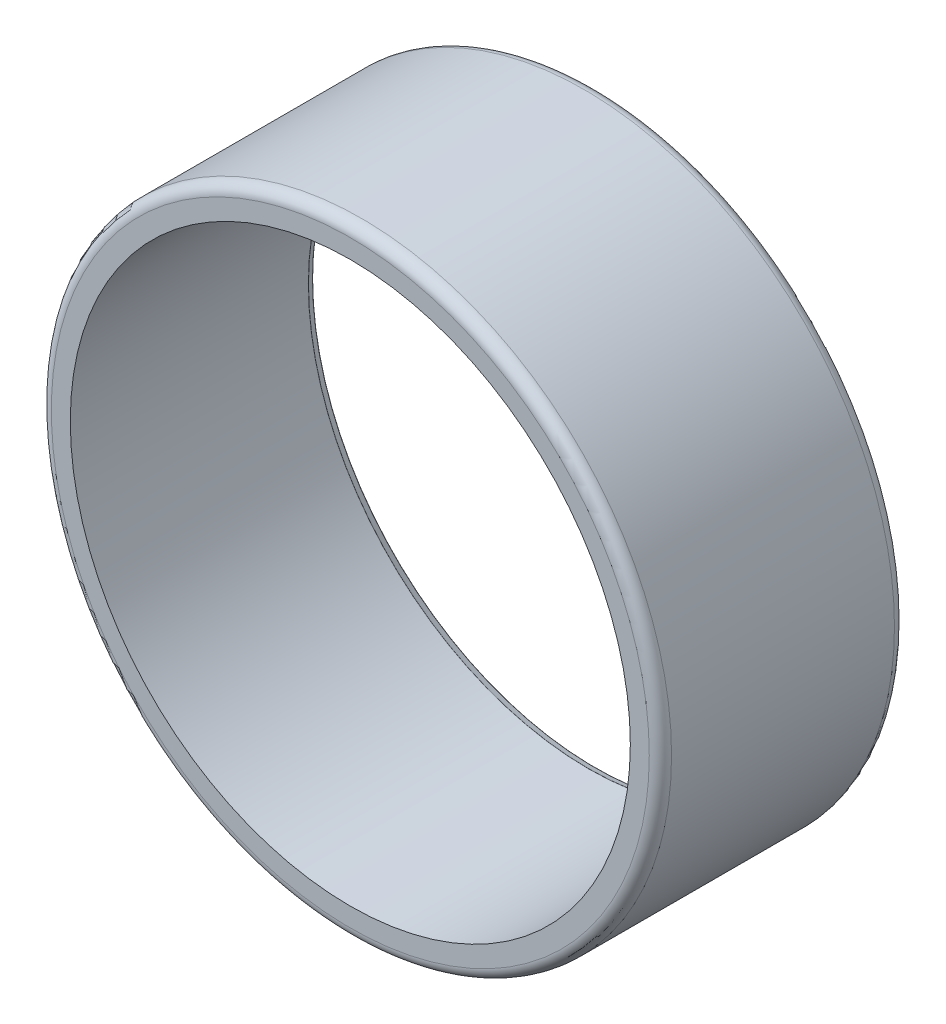
SolidWorks part; units mm, degrees
material "AISI 1018 Low Carbon Steel"
ref_plane "Front Plane" through (0, 0, 0) normal (0, 0, 1) x (1, 0, 0)
ref_plane "Top Plane" through (0, 0, 0) normal (0, 1, 0) x (1, 0, 0)
ref_plane "Right Plane" through (0, 0, 0) normal (1, 0, 0) x (0, 0, -1)
ref_axis "CL" through (0, 0, 55) along (0, 0, -1)
sketch "Sketch1" plane through (0, 0, 0) normal (1, 0, 0) x (0, 0, -1)
  line L0 (0, 27.825) -> (0, 0) construction
  line L1 (-9.96, 0) -> (9.96, 0) construction
  line L2 (-10, 27.825) -> (10, 27.825)
  line L3 (-11, 26.825) -> (-11, 25.125)
  line L4 (-11, 25.125) -> (11, 25.125)
  line L7 (11, 26.825) -> (11, 25.125)
  line L8 (10.3681, 25.125) -> (11, 25.355)
  arc A0 (-10, 27.825) -> (-11, 26.825) centre (-10, 26.825) ccw
  arc A1 (10, 27.825) -> (11, 26.825) centre (10, 26.825) cw
  point P9 (0, 0)
  point P13 (-11, 27.825)
  point P16 (11, 27.825)
  dimension "D4" = 1
  dimension "D5" = 1
  dimension "D1" = 50.25
  dimension "D2" = 22
  dimension "D3" = 55.65
  dimension "D6" = 20
  dimension "D7" = 0.23
revolve "Revolve1" add sketch "Sketch1" angle 360 about axis through (0, 0, 55) along (0, 0, -1)
fillet "Fillet1" radius 0.1 2 edges at (25.125, 0, -10.3681) (25.355, 0, -11)
